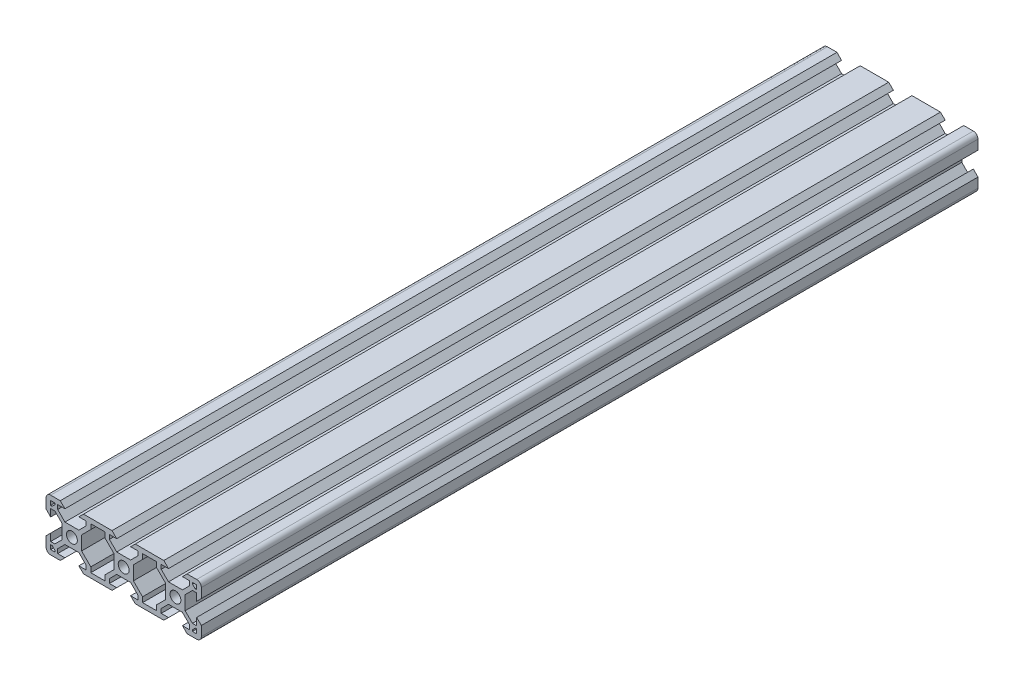
SolidWorks part; units mm, degrees
material "5052-H38, Barre (SS)"
ref_plane "Plan de face" through (0, 0, 0) normal (0, 0, 1) x (1, 0, 0)
ref_plane "Plan de dessus" through (0, 0, 0) normal (0, 1, 0) x (1, 0, 0)
ref_plane "Plan de droite" through (0, 0, 0) normal (1, 0, 0) x (0, 0, -1)
sketch "Esquisse1" plane through (0, 0, 0) normal (0, 0, 1) x (1, 0, 0)
  line L0 (0, 0) -> (-30, 0) construction
  line L1 (0, 0) -> (0, 10) construction
  line L2 (-20, 0) -> (-30, 10) construction
  line L3 (-20, 3.7507) -> (-22.69, 3.7507)
  line L4 (-22.69, 3.7507) -> (-25.4993, 6.56)
  line L5 (-25.4993, 6.56) -> (-25.4993, 8.2)
  line L6 (-25.4993, 8.2) -> (-22.69, 8.2)
  line L7 (-22.69, 8.2) -> (-24.49, 10)
  line L8 (-24.49, 10) -> (-28.2, 10)
  line L9 (-20, 0) -> (-20, 10) construction
  line L10 (-30, 4.49) -> (-30, 8.2)
  line L11 (-28.2, 2.69) -> (-30, 4.49)
  line L12 (-28.2, 5.4993) -> (-28.2, 2.69)
  line L13 (-26.56, 5.4993) -> (-28.2, 5.4993)
  line L14 (-23.7507, 2.69) -> (-26.56, 5.4993)
  line L15 (-23.7507, 0) -> (-23.7507, 2.69)
  line L16 (-28.2, 8.2) -> (-28.2, 6.5693)
  line L17 (-28.2, 6.5693) -> (-27.63, 6.5693)
  line L18 (-27.63, 6.5693) -> (-26.5693, 7.63)
  line L19 (-26.5693, 7.63) -> (-26.5693, 8.2)
  line L20 (-26.5693, 8.2) -> (-28.2, 8.2)
  line L21 (-23.7507, 0) -> (-23.7507, -2.69)
  line L22 (-23.7507, -2.69) -> (-26.56, -5.4993)
  line L23 (-26.56, -5.4993) -> (-28.2, -5.4993)
  line L24 (-28.2, -5.4993) -> (-28.2, -2.69)
  line L25 (-28.2, -2.69) -> (-30, -4.49)
  line L26 (-30, -4.49) -> (-30, -8.2)
  line L27 (-24.49, -10) -> (-28.2, -10)
  line L28 (-22.69, -8.2) -> (-24.49, -10)
  line L29 (-25.4993, -8.2) -> (-22.69, -8.2)
  line L30 (-25.4993, -6.56) -> (-25.4993, -8.2)
  line L31 (-22.69, -3.7507) -> (-25.4993, -6.56)
  line L32 (-20, -3.7507) -> (-22.69, -3.7507)
  line L33 (-26.5693, -7.63) -> (-27.63, -6.5693)
  line L34 (-27.63, -6.5693) -> (-28.2, -6.5693)
  line L35 (-28.2, -6.5693) -> (-28.2, -8.2)
  line L36 (-28.2, -8.2) -> (-26.5693, -8.2)
  line L37 (-26.5693, -8.2) -> (-26.5693, -7.63)
  line L38 (-2.69, -8.2) -> (-4.49, -10)
  line L39 (-2.69, 8.2) -> (-4.49, 10)
  line L40 (-7.3007, -8.2) -> (-7.3007, -6.24)
  line L41 (-7.3007, -6.24) -> (-3.7507, -2.69)
  line L42 (-3.7507, 2.69) -> (-3.7507, -2.69)
  line L43 (-7.3007, 6.24) -> (-3.7507, 2.69)
  line L44 (-7.3007, 8.2) -> (-7.3007, 6.24)
  line L45 (26.5693, 8.2) -> (28.2, 8.2)
  line L46 (26.5693, 7.63) -> (26.5693, 8.2)
  line L47 (27.63, 6.5693) -> (26.5693, 7.63)
  line L48 (28.2, 6.5693) -> (27.63, 6.5693)
  line L49 (28.2, 8.2) -> (28.2, 6.5693)
  line L50 (26.5693, -8.2) -> (26.5693, -7.63)
  line L51 (28.2, -8.2) -> (26.5693, -8.2)
  line L52 (28.2, -6.5693) -> (28.2, -8.2)
  line L53 (27.63, -6.5693) -> (28.2, -6.5693)
  line L54 (26.5693, -7.63) -> (27.63, -6.5693)
  line L55 (7.3007, 8.2) -> (7.3007, 6.24)
  line L56 (7.3007, 8.2) -> (12.6993, 8.2)
  line L57 (12.6993, 8.2) -> (12.6993, 6.24)
  line L58 (12.6993, 6.24) -> (16.2493, 2.69)
  line L59 (16.2493, 2.69) -> (16.2493, -2.69)
  line L60 (12.6993, -6.24) -> (16.2493, -2.69)
  line L61 (12.6993, -8.2) -> (12.6993, -6.24)
  line L62 (7.3007, -8.2) -> (12.6993, -8.2)
  line L63 (7.3007, -8.2) -> (7.3007, -6.24)
  line L64 (7.3007, -6.24) -> (3.7507, -2.69)
  line L65 (3.7507, 2.69) -> (3.7507, -2.69)
  line L66 (7.3007, 6.24) -> (3.7507, 2.69)
  line L67 (2.69, -8.2) -> (4.49, -10)
  line L68 (15.51, -10) -> (4.49, -10)
  line L69 (17.31, -8.2) -> (15.51, -10)
  line L70 (14.5007, -8.2) -> (17.31, -8.2)
  line L71 (14.5007, -6.56) -> (14.5007, -8.2)
  line L72 (17.31, -3.7507) -> (14.5007, -6.56)
  line L73 (20, -3.7507) -> (17.31, -3.7507)
  line L74 (20, -3.7507) -> (22.69, -3.7507)
  line L75 (22.69, -3.7507) -> (25.4993, -6.56)
  line L76 (25.4993, -6.56) -> (25.4993, -8.2)
  line L77 (25.4993, -8.2) -> (22.69, -8.2)
  line L78 (22.69, -8.2) -> (24.49, -10)
  line L79 (24.49, -10) -> (28.2, -10)
  line L80 (30, -4.49) -> (30, -8.2)
  line L81 (28.2, -2.69) -> (30, -4.49)
  line L82 (28.2, -5.4993) -> (28.2, -2.69)
  line L83 (26.56, -5.4993) -> (28.2, -5.4993)
  line L84 (0, 0) -> (-10, 10) construction
  line L85 (-17.31, 3.7507) -> (-14.5007, 6.56)
  line L86 (-14.5007, 6.56) -> (-14.5007, 8.2)
  line L87 (-14.5007, 8.2) -> (-17.31, 8.2)
  line L88 (-17.31, 8.2) -> (-15.51, 10)
  line L89 (-20, 3.7507) -> (-17.31, 3.7507)
  line L90 (-20, -3.7507) -> (-17.31, -3.7507)
  line L91 (-17.31, -3.7507) -> (-14.5007, -6.56)
  line L92 (-14.5007, -6.56) -> (-14.5007, -8.2)
  line L93 (-14.5007, -8.2) -> (-17.31, -8.2)
  line L94 (-17.31, -8.2) -> (-15.51, -10)
  line L95 (-10, 10) -> (-10, 0) construction
  line L96 (-15.51, 10) -> (-4.49, 10)
  line L97 (-15.51, -10) -> (-4.49, -10)
  line L98 (-7.3007, 8.2) -> (-12.6993, 8.2)
  line L99 (-12.6993, 8.2) -> (-12.6993, 6.24)
  line L100 (-12.6993, 6.24) -> (-16.2493, 2.69)
  line L101 (-16.2493, 2.69) -> (-16.2493, -2.69)
  line L102 (-20, 0) -> (-10, 10) construction
  line L103 (-17.31, 3.7507) -> (-16.2493, 2.69) construction
  line L104 (-12.6993, -6.24) -> (-16.2493, -2.69)
  line L105 (-12.6993, -8.2) -> (-12.6993, -6.24)
  line L106 (-7.3007, -8.2) -> (-12.6993, -8.2)
  line L107 (23.7507, -2.69) -> (26.56, -5.4993)
  line L108 (23.7507, 0) -> (23.7507, -2.69)
  line L109 (23.7507, 0) -> (23.7507, 2.69)
  line L110 (23.7507, 2.69) -> (26.56, 5.4993)
  line L111 (26.56, 5.4993) -> (28.2, 5.4993)
  line L112 (28.2, 5.4993) -> (28.2, 2.69)
  line L113 (28.2, 2.69) -> (30, 4.49)
  line L114 (30, 4.49) -> (30, 8.2)
  line L115 (24.49, 10) -> (28.2, 10)
  line L116 (22.69, 8.2) -> (24.49, 10)
  line L117 (25.4993, 8.2) -> (22.69, 8.2)
  line L118 (25.4993, 6.56) -> (25.4993, 8.2)
  line L119 (22.69, 3.7507) -> (25.4993, 6.56)
  line L120 (20, 3.7507) -> (22.69, 3.7507)
  line L121 (20, 3.7507) -> (17.31, 3.7507)
  line L122 (17.31, 3.7507) -> (14.5007, 6.56)
  line L123 (14.5007, 6.56) -> (14.5007, 8.2)
  line L124 (14.5007, 8.2) -> (17.31, 8.2)
  line L125 (17.31, 8.2) -> (15.51, 10)
  line L126 (15.51, 10) -> (4.49, 10)
  line L127 (2.69, 8.2) -> (4.49, 10)
  line L128 (-2.69, 8.2) -> (-5.4993, 8.2)
  line L129 (-5.4993, 8.2) -> (-5.4993, 6.56)
  line L130 (-5.4993, 6.56) -> (-2.69, 3.7507)
  line L131 (-2.69, 3.7507) -> (2.69, 3.7507)
  line L132 (5.4993, 6.56) -> (2.69, 3.7507)
  line L133 (5.4993, 8.2) -> (5.4993, 6.56)
  line L134 (5.4993, 8.2) -> (2.69, 8.2)
  line L135 (2.69, 8.2) -> (5.4993, 8.2)
  line L136 (5.4993, -8.2) -> (2.69, -8.2)
  line L137 (5.4993, -8.2) -> (5.4993, -6.56)
  line L138 (5.4993, -6.56) -> (2.69, -3.7507)
  line L139 (-2.69, -3.7507) -> (2.69, -3.7507)
  line L140 (-5.4993, -6.56) -> (-2.69, -3.7507)
  line L141 (-5.4993, -8.2) -> (-5.4993, -6.56)
  line L142 (-2.69, -8.2) -> (-5.4993, -8.2)
  circle A0 centre (0, 0) radius 2.1
  circle A1 centre (-20, 0) radius 2.1
  arc A2 (-28.2, 10) -> (-30, 8.2) centre (-28.2, 8.2) ccw
  arc A3 (-30, -8.2) -> (-28.2, -10) centre (-28.2, -8.2) ccw
  circle A4 centre (20, 0) radius 2.1
  arc A5 (30, -8.2) -> (28.2, -10) centre (28.2, -8.2) cw
  arc A6 (28.2, 10) -> (30, 8.2) centre (28.2, 8.2) cw
  point P26 (-27.0997, 7.0997)
  point P32 (-10, -10)
  point P55 (-10, -8.2)
  point P61 (-10, 8.2)
  point P106 (-16.7797, 3.2203)
  point P108 (-16.2493, 0)
  point P153 (0, 3.7507)
  point P154 (0, 3.7507)
  dimension "D3" = 4.2
  dimension "D1" = 30
  dimension "D2" = 10
  dimension "D5" = 20
  dimension "D6" = 1.5
  dimension "D7" = 1.64
  dimension "D8" = 1.8
  dimension "D9" = 5.38
  dimension "D10" = 1.07
  dimension "D12" = 45
  dimension "D15" = 1.96
  dimension "D4" = 2
  dimension "D11" = 2
  dimension "D13" = 2
  dimension "D14" = 2
extrude "Boss.-Extru.1" add sketch "Esquisse1" along normal mid plane 300 contours A6 L115 L116 L117 L118 L119 L120 L121 L122 L123 L124 L125 L126 L127 L134 L133 L132 L131 L130 L129 L128 L39 L96 L88 L87 L86 L85 L89 L3 L4 L5 L6 L7 L8 A2 L10 L11 L12 L13 L14 L15 L21 L22 L23 L24 L25 L26 A3 L27 L28 L29
